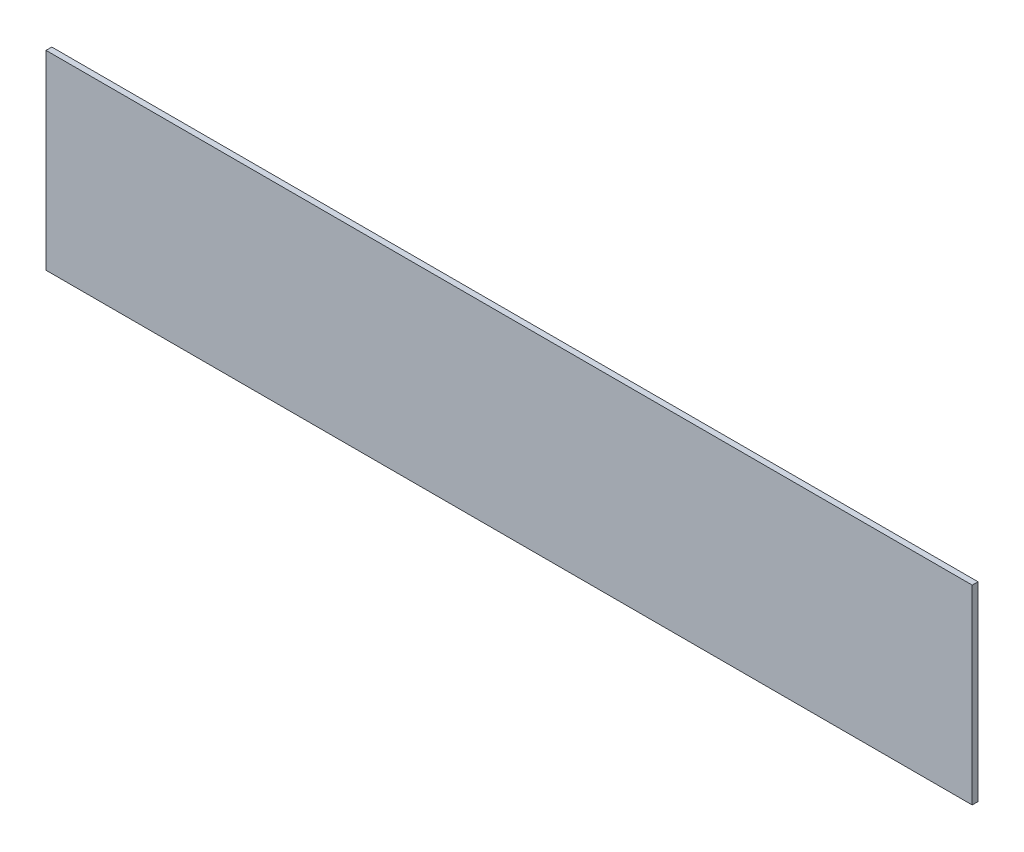
SolidWorks part; units mm, degrees
ref_plane "Front" through (0, 0, 0) normal (0, 0, 1) x (1, 0, 0)
ref_plane "Top" through (0, 0, 0) normal (0, 1, 0) x (1, 0, 0)
ref_plane "Right" through (0, 0, 0) normal (1, 0, 0) x (0, 0, -1)
sketch "Sketch1" plane through (0, 0, 0) normal (0, 0, 1) x (1, 0, 0)
  line L1 (-46.6126, -26.6194) -> (156.5874, -26.6194)
  line L2 (-46.6126, -26.6194) -> (-46.6126, 15.1636)
  line L3 (-46.6126, 15.1636) -> (156.5874, 15.1636)
  line L4 (156.5874, -26.6194) -> (156.5874, 15.1636)
  dimension "D1" = 41.783
  dimension "D2" = 203.2
extrude "Boss-Extrude1" add sketch "Sketch1" along normal blind 1.27
